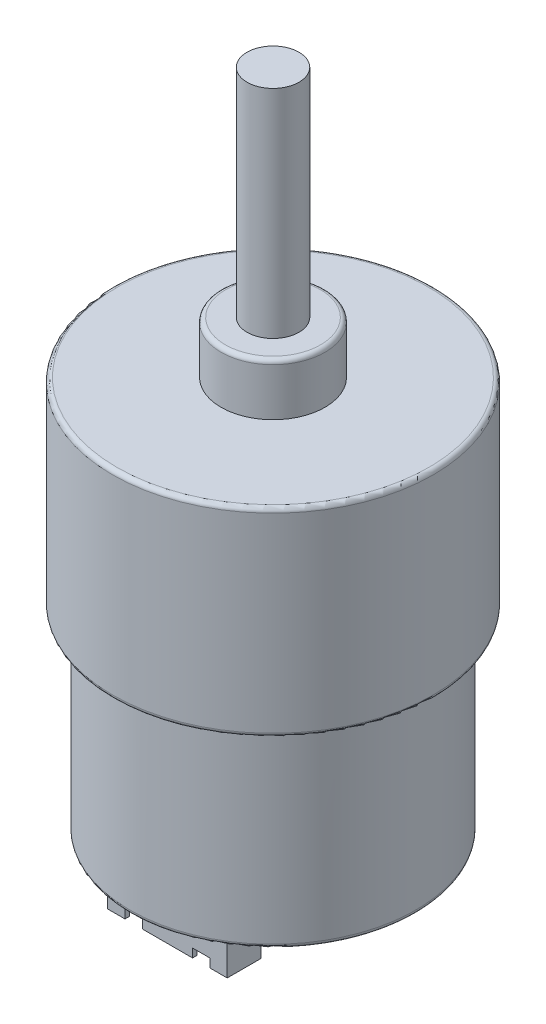
SolidWorks part; units mm, degrees
ref_plane "Front Plane" through (0, 0, 0) normal (0, 0, 1) x (1, 0, 0)
ref_plane "Top Plane" through (0, 0, 0) normal (0, 1, 0) x (1, 0, 0)
ref_plane "Right Plane" through (0, 0, 0) normal (1, 0, 0) x (0, 0, -1)
sketch "Sketch1" plane through (0, 0, 0) normal (0, 1, 0) x (1, 0, 0)
  circle A0 centre (0, 0) radius 16.5
  dimension "D1" = 33
extrude "Boss-Extrude1" add sketch "Sketch1" along normal blind 22.5
sketch "Sketch2" plane through (0, 22.5, 0) normal (0, 1, 0) x (1, 0, 0)
  circle A0 centre (0, 0) radius 18.5
  dimension "D1" = 37
extrude "Boss-Extrude2" add sketch "Sketch2" along normal blind 23
sketch "Sketch3" plane through (0, 45.5, 0) normal (0, 1, 0) x (1, 0, 0)
  line L0 (0, 0) -> (0, 0.01) construction
  circle A0 centre (0, 0.01) radius 6
  dimension "D2" = 12
  dimension "D1" = 0.01
extrude "Boss-Extrude3" add sketch "Sketch3" along normal blind 6
sketch "Sketch4" plane through (0, 51.5, 0) normal (0, 1, 0) x (1, 0, 0)
  circle A0 centre (0, 0.01) radius 3
  dimension "D1" = 6
extrude "Boss-Extrude4" add sketch "Sketch4" along normal blind 25
sketch "Sketch5" plane through (0, 76.5, 0) normal (0, 1, 0) x (1, 0, 0)
  line L1 (0, 2.8758) -> (-0.8871, 2.8758)
  line L2 (0, 2.8758) -> (0.8871, 2.8758)
  circle A0 centre (0, 0.01) radius 3 construction
  arc A2 (-0.8871, 2.8758) -> (0.8871, 2.8758) centre (0, 0.01) ccw
fillet "Fillet4" radius 0.5 1 edges at (0, 22.5, 18.5)
fillet "Fillet5" radius 0.5 1 edges at (0, 0, 16.5)
fillet "Fillet6" radius 0.5 1 edges at (0, 45.5, 18.5)
fillet "Fillet7" radius 0.5 1 edges at (0, 51.5, 5.99)
sketch "Sketch9" plane through (0, 0, 0) normal (0, -1, 0) x (1, 0, 0)
  circle A0 centre (0, 0) radius 5
  dimension "D1" = 10
extrude "Boss-Extrude5" add sketch "Sketch9" along normal blind 2
sketch "Sketch10" plane through (0, -2, 0) normal (0, -1, 0) x (1, 0, 0)
  circle A0 centre (0, 0) radius 1
  dimension "D1" = 2
extrude "Boss-Extrude6" add sketch "Sketch10" along normal blind 1
sketch "Sketch11" plane through (0, 0, 0) normal (0, -1, 0) x (1, 0, 0)
  line L0 (0, 5) -> (0, 16) construction
  line L1 (-6.9017, 12.1792) -> (6.9017, 12.1792)
  line L2 (-6.9017, 12.1792) -> (-6.9017, 8.2695)
  line L3 (-6.9017, 8.2695) -> (6.9017, 8.2695)
  line L4 (6.9017, 12.1792) -> (6.9017, 8.2695)
  line L5 (-6.4017, 11.6792) -> (6.4017, 11.6792)
  line L6 (6.4017, 11.6792) -> (6.4017, 8.7695)
  line L7 (-6.4017, 8.7695) -> (6.4017, 8.7695)
  line L8 (-6.4017, 11.6792) -> (-6.4017, 8.7695)
  circle A0 centre (0, 0) radius 5 construction
  circle A1 centre (0, 0) radius 5 construction
  circle A2 centre (0, 0) radius 16 construction
  dimension "D1" = 0.5
extrude "Boss-Extrude7" add sketch "Sketch11" along normal blind 5
sketch "Sketch12" plane through (0, 0, 12.1792) normal (0, 0, 1) x (1, 0, 0)
  line L0 (6.9017, -5) -> (-6.9017, -5) construction
  line L1 (-4.9017, -5) -> (-2.9017, -5)
  line L2 (-4.9017, -5) -> (-4.9017, -4)
  line L3 (-4.9017, -4) -> (-2.9017, -4)
  line L4 (-2.9017, -5) -> (-2.9017, -4)
  line L5 (-6.9017, -5) -> (-6.9017, 0) construction
  line L6 (0, -5) -> (0, -7.1224) construction
  line L7 (2.9017, -5) -> (2.9017, -4)
  line L8 (4.9017, -4) -> (2.9017, -4)
  line L9 (4.9017, -5) -> (4.9017, -4)
  line L10 (4.9017, -5) -> (2.9017, -5)
  dimension "D1" = 1
  dimension "D2" = 2
  dimension "D3" = 2
extrude "Cut-Extrude5" cut sketch "Sketch12" against normal blind 2
sketch "Sketch13" plane through (0, 0, 0) normal (0, -1, 0) x (1, 0, 0)
  line L0 (-6.4017, 10.2244) -> (6.4017, 10.2244) construction
  line L1 (-6.4017, 11.6792) -> (-6.4017, 8.7695) construction
  line L2 (6.4017, 8.7695) -> (6.4017, 11.6792) construction
  line L3 (-6.4017, 11.6792) -> (-6.4017, 8.7695) construction
  line L4 (-4.9017, 9.9744) -> (-4.4017, 9.9744)
  line L5 (-4.9017, 9.9744) -> (-4.9017, 10.4744)
  line L6 (-4.9017, 10.4744) -> (-4.4017, 10.4744)
  line L7 (-4.4017, 9.9744) -> (-4.4017, 10.4744)
  line L8 (-4.9017, 9.9744) -> (-4.4017, 10.4744) construction
  line L9 (-4.9017, 10.4744) -> (-4.4017, 9.9744) construction
  line L10 (-1.4017, 9.9744) -> (-1.4017, 10.4744)
  line L11 (-1.9017, 10.4744) -> (-1.4017, 10.4744)
  line L12 (-1.9017, 9.9744) -> (-1.9017, 10.4744)
  line L13 (-1.9017, 9.9744) -> (-1.4017, 9.9744)
  line L14 (1.5983, 9.9744) -> (1.5983, 10.4744)
  line L15 (1.0983, 10.4744) -> (1.5983, 10.4744)
  line L16 (1.0983, 9.9744) -> (1.0983, 10.4744)
  line L17 (1.0983, 9.9744) -> (1.5983, 9.9744)
  line L18 (4.5983, 9.9744) -> (4.5983, 10.4744)
  line L19 (4.0983, 10.4744) -> (4.5983, 10.4744)
  line L20 (4.0983, 9.9744) -> (4.0983, 10.4744)
  line L21 (4.0983, 9.9744) -> (4.5983, 9.9744)
  point P6 (-4.6517, 10.2244)
  dimension "D1" = 0.5
  dimension "D2" = 1.5
  dimension "D3" = 4
extrude "Boss-Extrude8" add sketch "Sketch13" along normal blind 4
